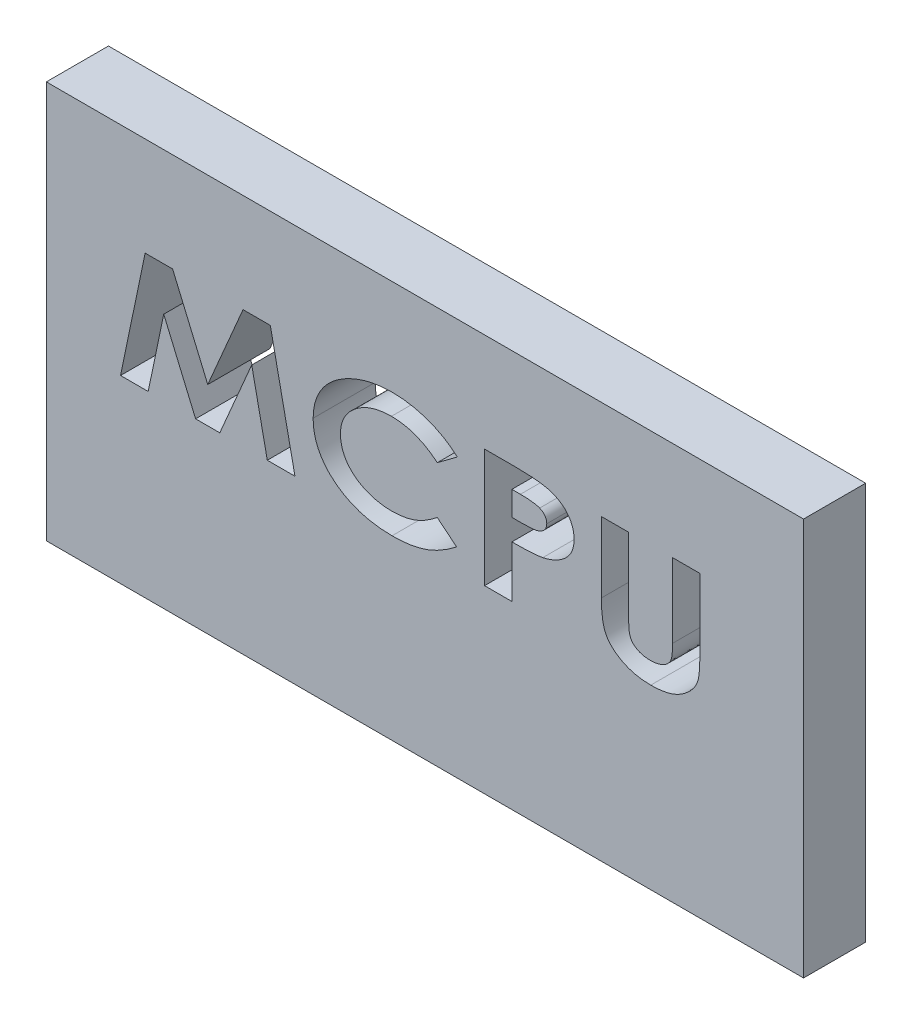
SolidWorks part; units mm, degrees
material "PBT General Purpose"
ref_plane "Front Plane" through (0, 0, 0) normal (0, 0, 1) x (1, 0, 0)
ref_plane "Top Plane" through (0, 0, 0) normal (0, 1, 0) x (1, 0, 0)
ref_plane "Right Plane" through (0, 0, 0) normal (1, 0, 0) x (0, 0, -1)
sketch "Sketch1" plane through (0, 0, 0) normal (0, 0, 1) x (1, 0, 0)
  line L0 (0, 0) -> (0, 32)
  line L1 (0, 32) -> (60.96, 32)
  line L2 (60.96, 32) -> (60.96, 0)
  line L3 (60.96, 0) -> (0, 0)
extrude "Boss-Extrude1" add sketch "Sketch1" along normal blind 5 contours L0 L1 L2 L3
sketch "Sketch2" plane through (0, 0, 5) normal (0, 0, 1) x (1, 0, 0)
  text T0 "MCPU" font "Century Gothic" height in points 36
extrude "Cut-Extrude1" cut sketch "Sketch2" against normal through all
